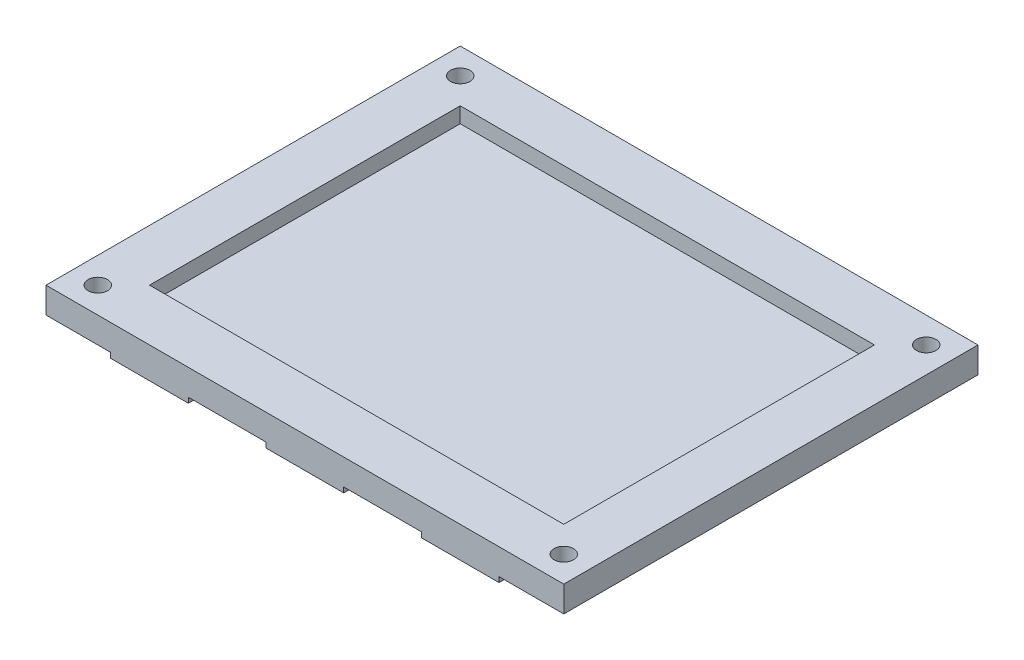
SolidWorks part; units mm, degrees
ref_plane "Front Plane" through (0, 0, 0) normal (0, 0, 1) x (1, 0, 0)
ref_plane "Top Plane" through (0, 0, 0) normal (0, 1, 0) x (1, 0, 0)
ref_plane "Right Plane" through (0, 0, 0) normal (1, 0, 0) x (0, 0, -1)
sketch "Sketch1" plane through (0, 0, 0) normal (0, 1, 0) x (1, 0, 0)
  line L1 (100, -80) -> (-100, -80)
  line L2 (100, -80) -> (100, 80)
  line L3 (100, 80) -> (-100, 80)
  line L4 (-100, -80) -> (-100, 80)
  line L5 (100, -80) -> (-100, 80) construction
  line L6 (100, 80) -> (-100, -80) construction
  point P0 (0, 0)
  dimension "D1" = 200
  dimension "D2" = 160
extrude "Boss-Extrude3" add sketch "Sketch1" along normal blind 10
sketch "Sketch3" plane through (0, 10, 0) normal (0, 1, 0) x (1, 0, 0)
  line L0 (-100, 80) -> (-80, 60) construction
  line L1 (-80, 60) -> (80, 60)
  line L2 (-80, 60) -> (-80, -60)
  line L3 (-80, -60) -> (80, -60)
  line L4 (80, 60) -> (80, -60)
  line L5 (-80, 60) -> (80, -60) construction
  line L6 (-80, -60) -> (80, 60) construction
  line L7 (80, 60) -> (100, 80) construction
  line L8 (-80, -60) -> (-100, -80) construction
  line L12 (80, -60) -> (100, -80) construction
  circle A0 centre (-90, 70) radius 3.75
  circle A2 centre (90, -70) radius 3.75
  circle A4 centre (90, 70) radius 3.75
  circle A5 centre (-90, -70) radius 3.75
  point P0 (0, 0)
  dimension "D3" = 7.5
  dimension "D4" = 7.5
  dimension "D5" = 7.5
  dimension "D6" = 7.5
  dimension "D1" = 160
  dimension "D2" = 120
extrude "Cut-Extrude2" cut sketch "Sketch3" along direction (0, 1, 0) on the side against the normal blind 6
sketch "Sketch6" plane through (0, 4, 0) normal (0, 1, 0) x (1, 0, 0)
  circle A0 centre (-90, 70) radius 3.75
  circle A1 centre (90, 70) radius 3.75
  circle A2 centre (90, -70) radius 3.75
  circle A3 centre (-90, -70) radius 3.75
  dimension "D1" = 7.5
  dimension "D2" = 7.5
  dimension "D3" = 7.5
  dimension "D4" = 7.5
extrude "Cut-Extrude4" cut sketch "Sketch6" against normal through all
sketch "Sketch7" plane through (0, 0, 0) normal (0, -1, 0) x (-1, 0, 0)
  line L0 (-100, 80) -> (100, 80) construction
  line L1 (15, -80) -> (-15, -80)
  line L2 (15, -80) -> (15, 80)
  line L3 (15, 80) -> (-15, 80)
  line L4 (-15, -80) -> (-15, 80)
  line L5 (15, -80) -> (-15, 80) construction
  line L6 (15, 80) -> (-15, -80) construction
  line L7 (75, -80) -> (75, 80)
  line L8 (75, -80) -> (45, -80)
  line L9 (45, -80) -> (45, 80)
  line L10 (75, 80) -> (45, 80)
  line L11 (-45, -80) -> (-45, 80)
  line L12 (-45, -80) -> (-75, -80)
  line L13 (-75, -80) -> (-75, 80)
  line L14 (-45, 80) -> (-75, 80)
  point P0 (0, 0)
  dimension "D1" = 30
  dimension "D2" = 2
  dimension "D3" = 2
extrude "Boss-Extrude4" add sketch "Sketch7" along normal blind 2
